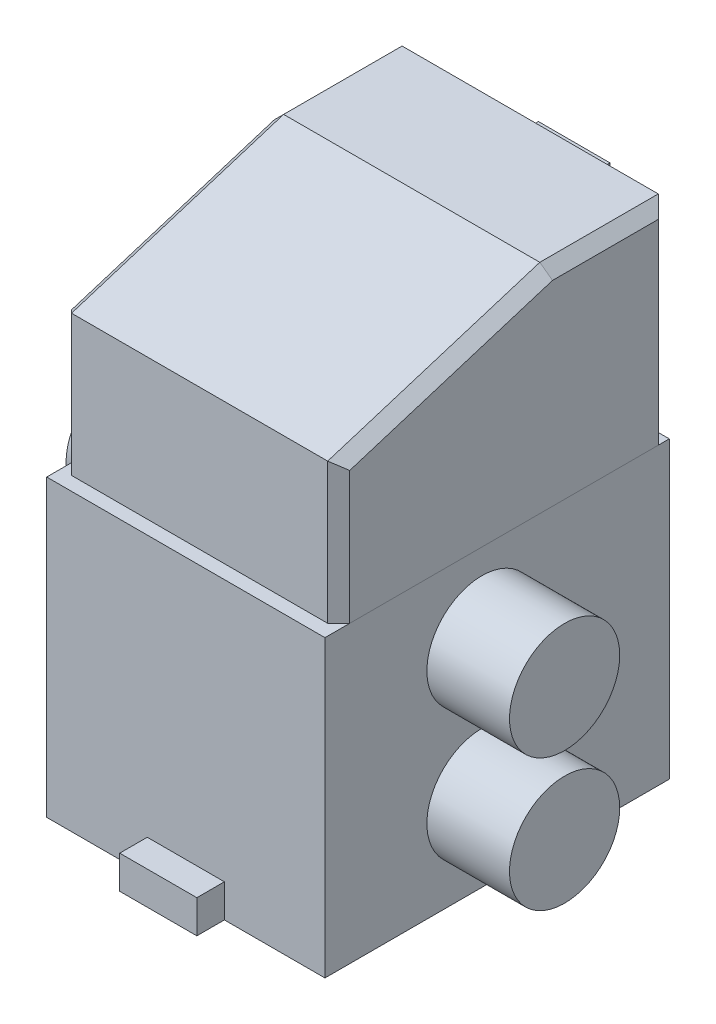
SolidWorks part; units mm, degrees
ref_plane "Front Plane" through (0, 0, 0) normal (0, 0, 1) x (1, 0, 0)
ref_plane "Top Plane" through (0, 0, 0) normal (0, 1, 0) x (1, 0, 0)
ref_plane "Right Plane" through (0, 0, 0) normal (1, 0, 0) x (0, 0, -1)
sketch "Sketch1" plane through (0, 0, 0) normal (0, 0, 1) x (1, 0, 0)
  line L1 (-252.5, 0) -> (252.5, 0)
  line L2 (-252.5, 0) -> (-252.5, 535)
  line L3 (-252.5, 535) -> (252.5, 535)
  line L4 (252.5, 0) -> (252.5, 535)
  dimension "D1" = 505
  dimension "D2" = 535
extrude "Boss-Extrude1" add sketch "Sketch1" along normal blind 625
sketch "Sketch2" plane through (0, 0, 0) normal (1, 0, 0) x (0, 0, -1)
  line L0 (-600, 0) -> (-675, 0)
  line L1 (-675, 0) -> (-675, 60)
  line L2 (-675, 60) -> (-600, 60)
  line L3 (-600, 60) -> (-600, 0)
  line L4 (-625, 0) -> (0, 0) construction
  line L6 (-85, 535) -> (-85, 0) construction
  line L7 (-625, 535) -> (0, 535) construction
  line L8 (-625, 0) -> (-625, 535) construction
  dimension "D1" = 540
  dimension "D2" = 515
  dimension "D3" = 75
  dimension "D4" = 60
extrude "Boss-Extrude2" add sketch "Sketch2" along normal mid plane 140
sketch "Sketch3" plane through (-252.5, 0, 0) normal (-1, 0, 0) x (0, 0, 1)
  line L0 (95, 535) -> (95, 0) construction
  line L1 (625, 535) -> (0, 535) construction
  line L2 (625, 0) -> (0, 0) construction
  line L3 (340, 535) -> (340, 0) construction
  line L4 (0, 535) -> (0, 0) construction
  circle A0 centre (340, 390) radius 100
  circle A1 centre (95, 190) radius 100
  circle A2 centre (340, 150) radius 100
  point P14 (215.5157, 434.0483)
  point P15 (143.7602, 221.0478)
  point P16 (215.5157, 79.8027)
  dimension "D3" = 200
  dimension "D1" = 95
  dimension "D2" = 340
  dimension "D4" = 150
  dimension "D5" = 190
  dimension "D6" = 390
extrude "Boss-Extrude3" add sketch "Sketch3" along normal blind 150 separate body
sketch "Sketch4" plane through (252.5, 0, 0) normal (1, 0, 0) x (0, 0, -1)
  circle A0 centre (-340, 390) radius 100
  circle A1 centre (-340, 150) radius 100
  circle A2 centre (-340, 390) radius 100 construction
  circle A3 centre (-340, 150) radius 100 construction
extrude "Boss-Extrude4" add sketch "Sketch4" along normal blind 150 separate body
sketch "Sketch5" plane through (0, 0, 0) normal (1, 0, 0) x (0, 0, -1)
  line L0 (-600, 790) -> (-600, 535)
  line L1 (-600, 535) -> (0, 535)
  line L2 (0, 535) -> (0, 910)
  line L3 (0, 910) -> (-215, 910)
  line L4 (-215, 910) -> (-600, 790)
  line L5 (-625, 535) -> (0, 535) construction
  line L7 (0, 0) -> (0, 535) construction
  dimension "D1" = 255
  dimension "D2" = 600
  dimension "D3" = 375
  dimension "D4" = 215
extrude "Boss-Extrude5" add sketch "Sketch5" along normal mid plane 505 separate body
chamfer "Chamfer1" distance 20 angle 45 8 edges at (-252.5, 722.5, 0) (-252.5, 910, 107.5) (-252.5, 850, 407.5) (-252.5, 662.5, 600) (252.5, 722.5, 0) (252.5, 910, 107.5) (252.5, 850, 407.5) (252.5, 662.5, 600)
sketch "Sketch6" plane through (0, 0, 0) normal (0, 0, -1) x (-1, 0, 0)
  line L0 (0, 97.1967) -> (0, 309.1807) construction
  line L1 (-65, 835) -> (65, 835)
  line L2 (-65, 835) -> (-65, 705)
  line L3 (-65, 705) -> (65, 705)
  line L4 (65, 835) -> (65, 705)
  line L5 (-232.5, 910) -> (232.5, 910) construction
  dimension "D1" = 130
  dimension "D2" = 130
  dimension "D3" = 75
extrude "Boss-Extrude6" add sketch "Sketch6" along normal blind 80
